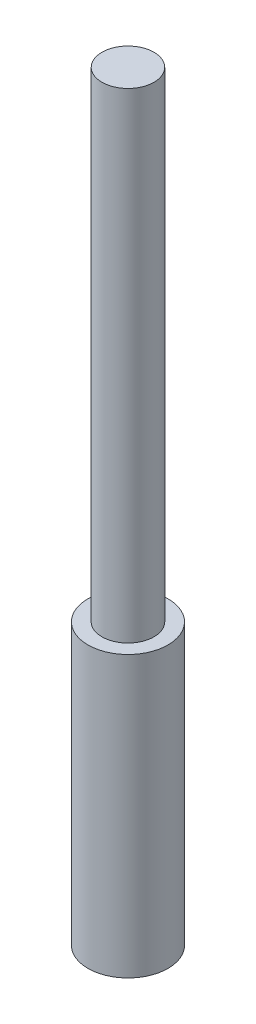
SolidWorks part; units mm, degrees
ref_plane "Front Plane" through (0, 0, 0) normal (0, 0, 1) x (1, 0, 0)
ref_plane "Top Plane" through (0, 0, 0) normal (0, 1, 0) x (1, 0, 0)
ref_plane "Right Plane" through (0, 0, 0) normal (1, 0, 0) x (0, 0, -1)
sketch "Sketch1" plane through (0, 0, 0) normal (0, 1, 0) x (1, 0, 0)
  circle A0 centre (0, 0) radius 5
  dimension "D1" = 10
extrude "Boss-Extrude1" add sketch "Sketch1" along normal blind 95
sketch "Sketch2" plane through (0, 95, 0) normal (0, 1, 0) x (1, 0, 0)
  circle A0 centre (0, 0) radius 3.25
  circle A1 centre (0, 0) radius 5
  circle A2 centre (0, 0) radius 5 construction
  dimension "D1" = 6.5
extrude "Cut-Extrude1" cut sketch "Sketch2" against normal blind 60
